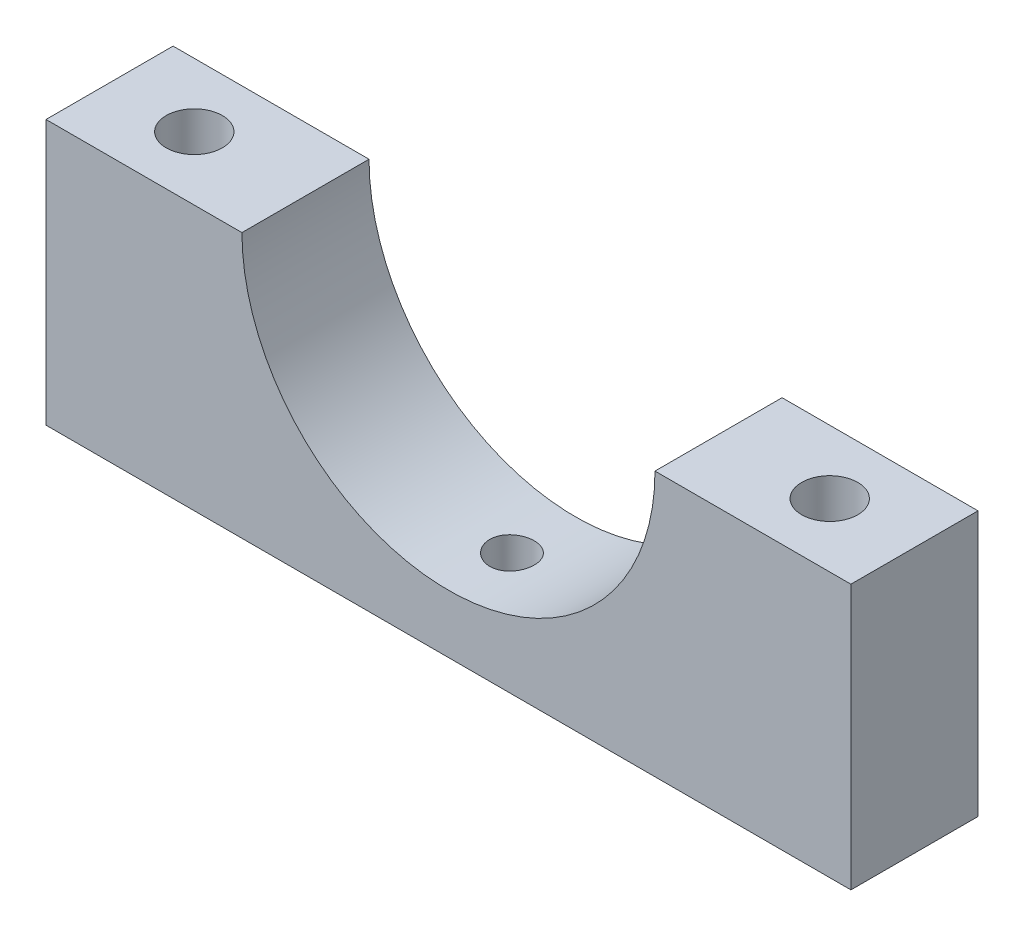
SolidWorks part; units mm, degrees
ref_plane "前视基准面" through (0, 0, 0) normal (0, 0, 1) x (1, 0, 0)
ref_plane "上视基准面" through (0, 0, 0) normal (0, 1, 0) x (1, 0, 0)
ref_plane "右视基准面" through (0, 0, 0) normal (1, 0, 0) x (0, 0, -1)
sketch "草图1" plane through (0, 0, 0) normal (0, 1, 0) x (1, 0, 0)
  line L0 (0, 0) -> (20.1906, 0) construction
  line L1 (0, 0) -> (0, 23.0129) construction
  line L3 (-38, 6) -> (38, 6)
  line L4 (-38, 6) -> (-38, -6)
  line L5 (-38, -6) -> (38, -6)
  line L6 (38, 6) -> (38, -6)
  dimension "D1" = 76
  dimension "D2" = 12
extrude "凸台-拉伸1" add sketch "草图1" against normal blind 25
sketch "草图2" plane through (0, 0, 6) normal (0, 0, 1) x (1, 0, 0)
  circle A0 centre (0, 0) radius 19.5
  dimension "D1" = 39
extrude "切除-拉伸1" cut sketch "草图2" against normal up to next
hole_wizard "M5 螺纹孔1" positions "草图4" profile "草图3" tap size "M5" standard "GB" end condition up to next
sketch "草图4" plane through (0, -25, 0) normal (0, -1, 0) x (1, 0, 0)
  point P0 (0, 0)
sketch "草图3" plane through (0, -25, 0) normal (1, 0, 0) x (0, 0, -1)
  line L0 (0, 0) -> (0, 5.5)
  line L1 (0, 5.5) -> (2.1, 5.5)
  line L2 (2.1, 5.5) -> (2.1, 0)
  line L5 (2.1, 0) -> (0, 0)
  line L11 (0, -6.35) -> (0, 13.021) construction
  dimension "通孔螺纹孔钻头直径" = 4.2
  dimension "通孔螺纹孔钻头深度" = 5.5
cosmetic thread "孔螺蚊线2" parameters "D1"=5.5902, "D2"=5
hole_wizard "打孔尺寸根据内六角圆柱头螺钉的类型1" positions "草图6" profile "草图5" counterbore size "M5" standard "GB" end condition through all
sketch "草图6" plane through (0, -25, 0) normal (0, -1, 0) x (1, 0, 0)
  line L0 (0, 0) -> (0, 9.576) construction
  line L1 (0, 0) -> (9.4287, 0) construction
  point P0 (-30, 0)
  point P11 (30, 0)
  dimension "D1" = 60
sketch "草图5" plane through (-30, -25, 0) normal (1, 0, 0) x (0, 0, -1)
  line L0 (0, 0) -> (0, 25)
  line L1 (0, 25) -> (2.65, 25)
  line L3 (2.65, 25) -> (2.65, 8.7)
  line L4 (2.65, 8.7) -> (5, 8.7)
  line L5 (5, 8.7) -> (5, 0)
  line L7 (5, 0) -> (0, 0)
  line L11 (0, -6.35) -> (0, 107.95) construction
  dimension "通孔孔直径" = 5.3
  dimension "通孔孔深度" = 25
  dimension "柱形沉头孔直径" = 10
  dimension "柱形沉头孔深度" = 8.7
